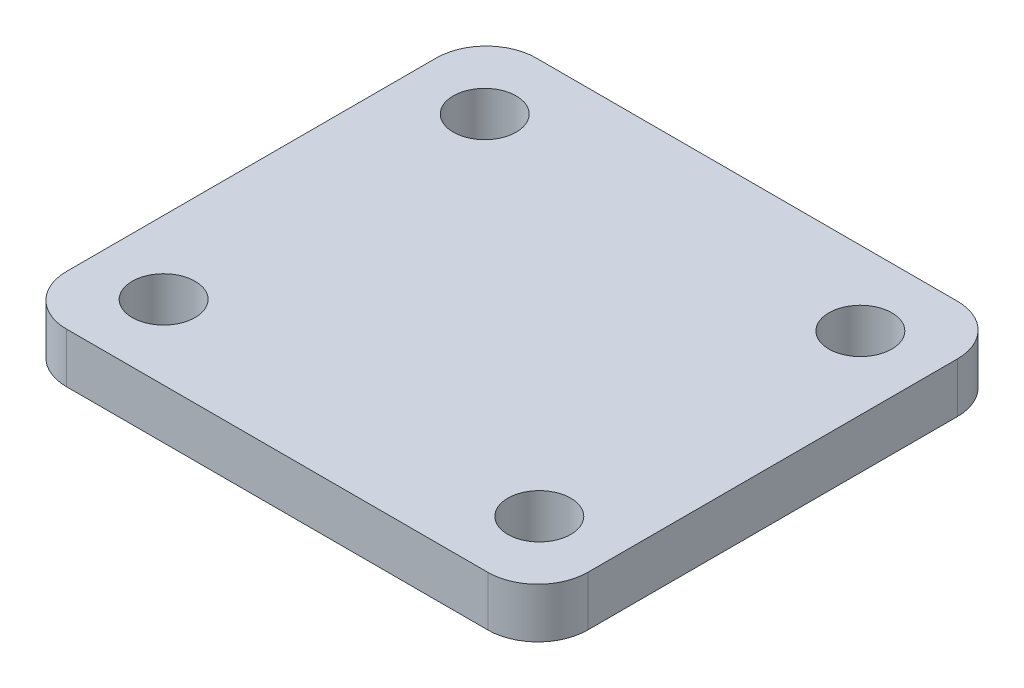
SolidWorks part; units mm, degrees
ref_plane "Front Plane" through (0, 0, 0) normal (0, 0, 1) x (1, 0, 0)
ref_plane "Top Plane" through (0, 0, 0) normal (0, 1, 0) x (1, 0, 0)
ref_plane "Right Plane" through (0, 0, 0) normal (1, 0, 0) x (0, 0, -1)
sketch "Sketch1" plane through (0, 0, 0) normal (0, 1, 0) x (1, 0, 0)
  line L1 (-10.71, -11.9375) -> (10.71, -11.9375)
  line L2 (-13.25, -9.3975) -> (-13.25, 9.3975)
  line L3 (-10.71, 11.9375) -> (10.71, 11.9375)
  line L4 (13.25, -9.3975) -> (13.25, 9.3975)
  arc A0 (10.71, 11.9375) -> (13.25, 9.3975) centre (10.71, 9.3975) cw
  arc A1 (10.71, -11.9375) -> (13.25, -9.3975) centre (10.71, -9.3975) ccw
  arc A2 (-10.71, -11.9375) -> (-13.25, -9.3975) centre (-10.71, -9.3975) cw
  arc A3 (-13.25, 9.3975) -> (-10.71, 11.9375) centre (-10.71, 9.3975) cw
  point P8 (13.25, 11.9375)
  point P11 (13.25, -11.9375)
  point P14 (-13.25, -11.9375)
  dimension "D5" = 2.54
  dimension "D1" = 26.5
  dimension "D2" = 23.875
  dimension "D3" = 13.25
  dimension "D4" = 11.9375
extrude "Boss-Extrude1" add sketch "Sketch1" along normal blind 2.54
sketch "Sketch2" plane through (0, 2.54, 0) normal (0, 1, 0) x (1, 0, 0)
  circle A0 centre (-9.55, 8.1625) radius 1.6
  circle A1 centre (9.55, 8.1625) radius 1.6
  circle A2 centre (9.55, -8.1625) radius 1.6
  circle A3 centre (-9.55, -8.1625) radius 1.6
  dimension "D1" = 3.2
  dimension "D2" = 3.2
  dimension "D3" = 3.2
  dimension "D4" = 3.2
  dimension "D6" = 0
  dimension "D5" = 19.1
  dimension "D7" = 19.1
  dimension "D8" = 0
  dimension "D9" = 16.325
  dimension "D10" = 0
  dimension "D11" = 9.55
  dimension "D12" = 8.1625
extrude "Cut-Extrude1" cut sketch "Sketch2" against normal through all
